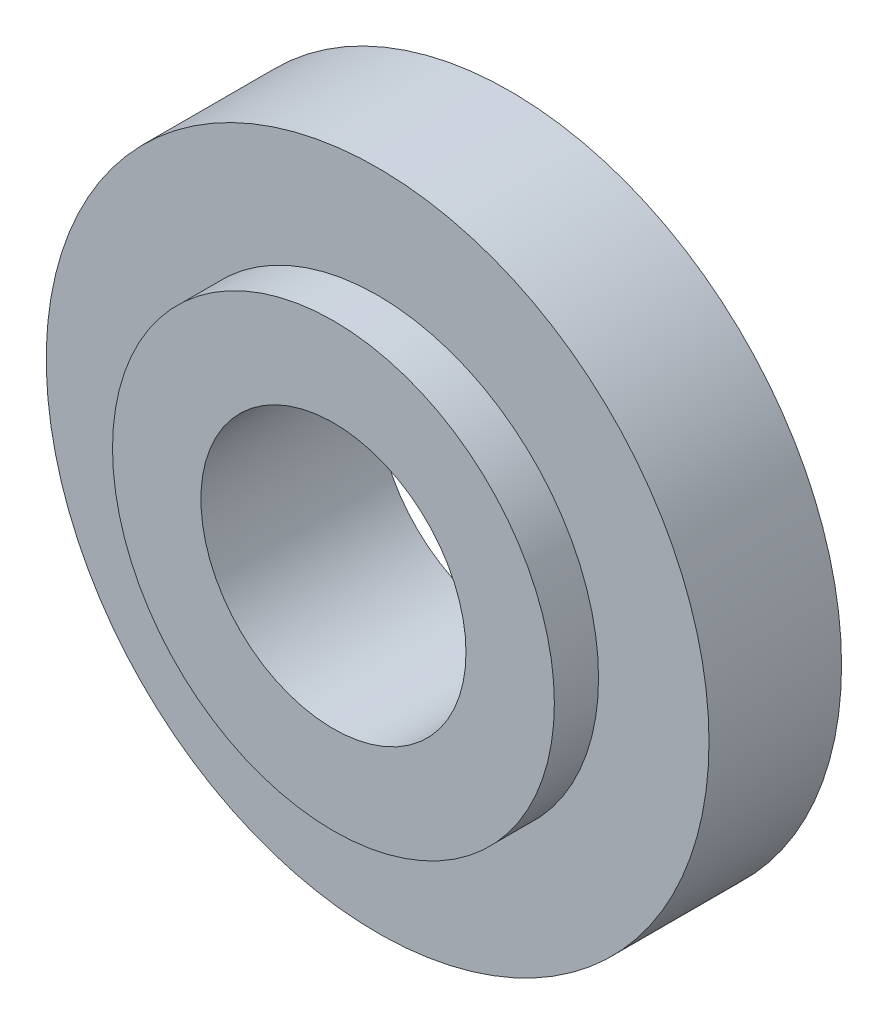
SolidWorks part; units mm, degrees
ref_plane "Front Plane" through (0, 0, 0) normal (0, 0, 1) x (1, 0, 0)
ref_plane "Top Plane" through (0, 0, 0) normal (0, 1, 0) x (1, 0, 0)
ref_plane "Right Plane" through (0, 0, 0) normal (1, 0, 0) x (0, 0, -1)
sketch "Sketch1" plane through (0, 0, 0) normal (0, 0, 1) x (1, 0, 0)
  circle A0 centre (0, 0) radius 3.75
  circle A1 centre (0, 0) radius 1.5
  dimension "D1" = 7.5
  dimension "D2" = 3
extrude "Boss-Extrude1" add sketch "Sketch1" along normal blind 1.5
sketch "Sketch2" plane through (0, 0, 1.5) normal (0, 0, 1) x (1, 0, 0)
  circle A0 centre (0, 0) radius 1.5 construction
  circle A1 centre (0, 0) radius 1.5
  circle A2 centre (0, 0) radius 2.5
extrude "Boss-Extrude2" add sketch "Sketch2" along normal blind 0.5
